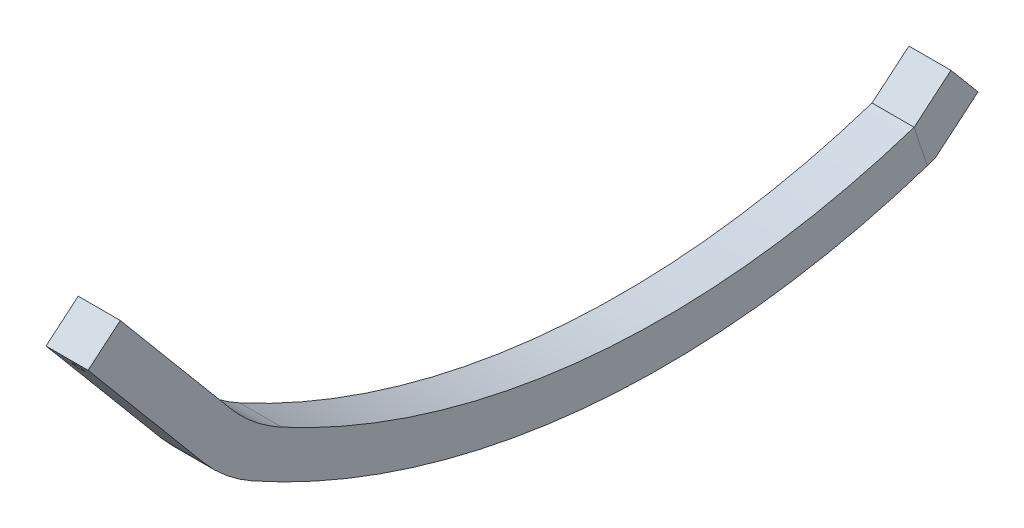
SolidWorks part; units mm, degrees
ref_plane "Ebene vorne" through (0, 0, 0) normal (0, 0, 1) x (1, 0, 0)
ref_plane "Ebene oben" through (0, 0, 0) normal (0, 1, 0) x (1, 0, 0)
ref_plane "Ebene rechts" through (0, 0, 0) normal (1, 0, 0) x (0, 0, -1)
sketch "Skizze1" plane through (0, 0, 0) normal (1, 0, 0) x (0, 0, -1)
  line L0 (0, 12) -> (-233.4212, 12) construction
  line L1 (-240, 65) -> (-230.7357, 72.7737)
  line L2 (0, 12) -> (-3.7358, 23.4037)
  line L3 (0, 12) -> (0, 39.1297) construction
  line L4 (0, 0) -> (-218.6687, 0) construction
  arc A0 (0, 12) -> (-240, 65) centre (-75.176, 241.4765) cw
  arc A1 (-3.7358, 23.4037) -> (-230.7357, 72.7737) centre (-75.176, 241.4765) cw
  dimension "D1" = 53
  dimension "D2" = 240
  dimension "D3" = 40
  dimension "D4" = 12
  dimension "D5" = 12
extrude "Aufsatz-Linear austragen1" add sketch "Skizze1" along normal blind 12
sketch "Skizze4" plane through (0, 0, 0) normal (1, 0, 0) x (0, 0, -1)
  line L0 (-230.7357, 72.7737) -> (-240, 65) construction
  line L2 (-3.7358, 23.4037) -> (6.769, 32.2183)
  line L3 (6.769, 32.2183) -> (14.4825, 23.0258)
  line L4 (14.4825, 23.0258) -> (2.2258, 12.7411)
  line L5 (-3.7358, 23.4037) -> (0, 12)
  arc A0 (0, 12) -> (2.2258, 12.7411) centre (-75.176, 241.4765) ccw
  arc A4 (-240, 65) -> (0, 12) centre (-75.176, 241.4765) ccw construction
  dimension "D1" = 16
  dimension "D2" = 12
extrude "Aufsatz-Linear austragen3" add sketch "Skizze4" along normal blind 12 separate body
sketch "Skizze5" plane through (12, 0, 0) normal (1, 0, 0) x (0, 0, -1)
  line L0 (-231.6625, 71.996) -> (-222.47, 79.7094)
  line L1 (-230.7357, 72.7737) -> (-232.109, 74.04) construction
  line L2 (-231.6625, 71.996) -> (-220.0923, 58.2072)
  line L3 (-230.7357, 72.7737) -> (-240, 65) construction
  line L4 (-222.47, 79.7094) -> (-210.8998, 65.9206)
  line L5 (-220.0923, 58.2072) -> (-192.9483, 44.5269)
  line L6 (-220.0923, 58.2072) -> (-211.3409, 65.5505) construction
  line L7 (-210.8998, 65.9206) -> (-192.9483, 44.5269)
  arc A6 (-230.7357, 72.7737) -> (-3.7358, 23.4037) centre (-75.176, 241.4765) ccw construction
  dimension "D1" = 12
  dimension "D2" = 1.2
  dimension "D3" = 18
extrude "Aufsatz-Linear austragen4" add sketch "Skizze5" against normal up to surface (12 mm away) up to face at (0, 27.378, 122.107)
sketch "Skizze6" plane through (12, 0, 0) normal (1, 0, 0) x (0, 0, -1)
  line L0 (-231.6625, 71.996) -> (-199.5106, 33.6789)
  line L1 (-199.5106, 33.6789) -> (-204.3677, 29.6033)
  line L2 (-204.3677, 29.6033) -> (-240, 65)
  line L3 (-240, 65) -> (-231.6625, 71.996)
extrude "Schnitt-Linear austragen1" cut sketch "Skizze6" against normal through all
sketch "Skizze7" plane through (12, 0, 0) normal (1, 0, 0) x (0, 0, -1)
  line L0 (-222.47, 79.7094) -> (-229.5406, 88.1359)
  line L1 (-192.9483, 44.5269) -> (-222.47, 79.7094) construction
  line L2 (-229.5406, 88.1359) -> (-238.7332, 80.4225)
  line L3 (-238.7332, 80.4225) -> (-231.6625, 71.996)
  line M4 (-222.47, 79.7094) -> (-231.6625, 71.996)
  dimension "D1" = 11
extrude "Aufsatz-Linear austragen5" [suppressed] add sketch "Skizze7" against normal up to surface (12 mm away) contours L2 L3 L0 M4
fillet "Verrundung1" radius 50 2 edges at (6, 35.2854, 200.8587) (6, 44.5269, 192.9483)
sketch "Skizze8" [suppressed] plane through (0, -76.6111, 91.3015) normal (0, 0.6428, -0.766) x (-1, 0, 0)
  line L0 (-6, 215.0619) -> (-6, 184.7045) construction
  line L1 (0, 215.0619) -> (-12, 215.0619) construction
  circle A0 centre (-6, 210.0619) radius 1.55
  dimension "D2" = 3.1
  dimension "D1" = 5
extrude "Schnitt-Linear austragen2" [suppressed] cut sketch "Skizze8" against normal blind 6
sketch "Skizze9" plane through (0, 156.3205, 131.1685) normal (0, 0.766, 0.6428) x (1, 0, 0)
  line L0 (6, -119.1857) -> (6, -131.1857) construction
  line L1 (0, -119.1857) -> (12, -119.1857) construction
  line L2 (0, -131.1857) -> (12, -131.1857) construction
  line L3 (12, -125.1857) -> (0, -125.1857) construction
  line L4 (12, -119.1857) -> (12, -131.1857) construction
  line L5 (0, -119.1857) -> (0, -131.1857) construction
  line L7 (0, -131.1857) -> (12, -131.1857)
  line L8 (0, -131.1857) -> (0, -119.1857)
  line L9 (0, -119.1857) -> (12, -119.1857)
  line L10 (12, -131.1857) -> (12, -119.1857)
  line L11 (0, -131.1857) -> (12, -119.1857) construction
  line L12 (0, -119.1857) -> (12, -131.1857) construction
  point P12 (6, -125.1857)
  dimension "D1" = 12
extrude "Aufsatz-Linear austragen6" add sketch "Skizze9" along normal blind 12
sketch "Skizze10" plane through (0, 16.6449, -19.8366) normal (0, 0.6428, -0.766) x (-1, 0, 0)
  line L0 (-6, 20.3296) -> (-6, 8.3296) construction
  line L1 (-12, 20.3296) -> (0, 20.3296) construction
  line L2 (-12, 8.3296) -> (0, 8.3296) construction
  line L4 (-11.9, 8.4296) -> (-0.1, 8.4296)
  line L5 (-11.9, 8.4296) -> (-11.9, 20.2296)
  line L6 (-11.9, 20.2296) -> (-0.1, 20.2296)
  line L7 (-0.1, 8.4296) -> (-0.1, 20.2296)
  line L8 (-11.9, 8.4296) -> (-0.1, 20.2296) construction
  line L9 (-11.9, 20.2296) -> (-0.1, 8.4296) construction
  circle A0 centre (-6, 14.3296) radius 9.0363
  point P6 (-6, 14.3296)
  dimension "D1" = 11.8
extrude "Schnitt-Linear austragen3" [suppressed] cut sketch "Skizze10" against normal blind 10
sketch "Skizze11" plane through (0, -76.6111, 91.3015) normal (0, 0.6428, -0.766) x (-1, 0, 0)
  line L0 (-6, 216.0619) -> (-6, 204.6824) construction
  line L1 (-12, 216.0619) -> (0, 216.0619) construction
  circle A0 centre (-6, 211.0619) radius 1.55
  dimension "D1" = 3.1
  dimension "D2" = 5
extrude "Schnitt-Linear austragen4" cut sketch "Skizze11" against normal through all
chamfer "Fase1" [suppressed] distance 0.1 angle 45
